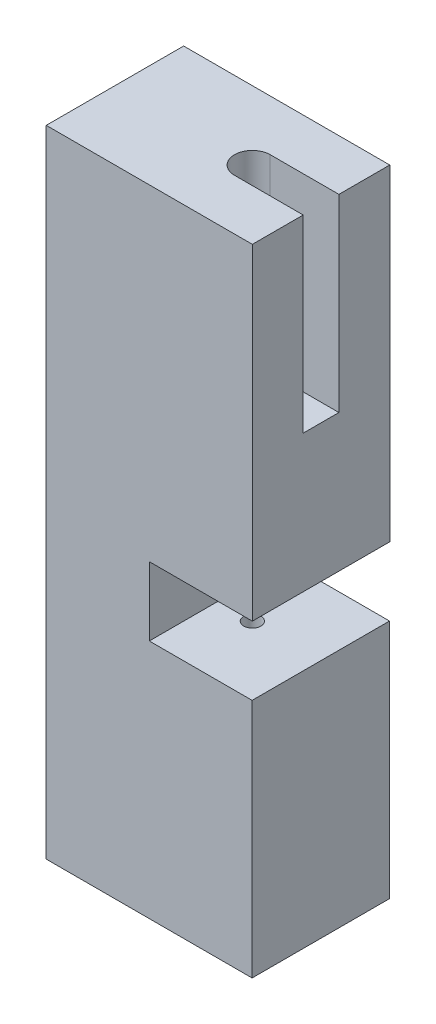
SolidWorks part; units mm, degrees
ref_plane "Front Plane" through (0, 0, 0) normal (0, 0, 1) x (1, 0, 0)
ref_plane "Top Plane" through (0, 0, 0) normal (0, 1, 0) x (1, 0, 0)
ref_plane "Right Plane" through (0, 0, 0) normal (1, 0, 0) x (0, 0, -1)
sketch "Sketch1" plane through (0, 0, 0) normal (0, 1, 0) x (1, 0, 0)
  line L1 (-19.05, -12.7) -> (19.05, -12.7)
  line L2 (-19.05, -12.7) -> (-19.05, 12.7)
  line L3 (-19.05, 12.7) -> (19.05, 12.7)
  line L4 (19.05, -12.7) -> (19.05, 12.7)
  line L5 (-19.05, -12.7) -> (19.05, 12.7) construction
  line L6 (-19.05, 12.7) -> (19.05, -12.7) construction
  point P0 (0, 0)
extrude "Boss-Extrude1" add sketch "Sketch1" along normal blind 25.4
sketch "Sketch2" plane through (0, 25.4, 0) normal (0, 1, 0) x (1, 0, 0)
  line L1 (19.05, -12.7) -> (19.05, 12.7) construction
  line L2 (19.05, 0) -> (6.35, 0) construction
  circle A0 centre (6.35, 0) radius 3.18
sketch "Sketch3" plane through (-19.05, 0, 0) normal (-1, 0, 0) x (0, 0, 1)
  line L0 (0, 0) -> (0, 25.4) construction
  line L1 (-12.7, 25.4) -> (12.7, 25.4) construction
  line L2 (12.7, 12.7) -> (-12.7, 12.7) construction
  line L3 (12.7, 25.4) -> (12.7, 0) construction
  line L4 (-12.7, 25.4) -> (-12.7, 0) construction
  circle A0 centre (0, 12.7) radius 1.5875
extrude "Cut-Extrude2" cut sketch "Sketch3" against normal blind 25.4
hole_wizard "1/4-28 Tapped Hole1" positions "Sketch5" profile "Sketch4" tap size "1/4-28" standard "ANSI Inch"
sketch "Sketch5" plane through (-19.05, 0, 0) normal (-1, 0, 0) x (0, 0, 1)
  point P0 (0, 12.7)
sketch "Sketch4" plane through (-19.05, 12.7, 0) normal (0, 1, 0) x (0, 0, 1)
  line L0 (0, 0) -> (0, 18.8554)
  line L1 (0, 18.8554) -> (2.7051, 17.23)
  line L2 (2.7051, 17.23) -> (2.7051, 0)
  line L5 (2.7051, 0) -> (0, 0)
  line L10 (0, 18.8554) -> (-2.7051, 17.23) construction
  line L11 (0, -6.35) -> (0, 107.95) construction
  dimension "Tap Drill Dia." = 5.4102
  dimension "Tap Drill Depth" = 17.23
  dimension "Drill Angle" = 118
cosmetic thread "Hole Thread1" parameters "D1"=12.7, "D2"=6.35
extrude "Cut-Extrude6" cut sketch "Sketch2" against normal blind 15.875 contours A0
sketch "Sketch8" plane through (0, 0, 0) normal (0, -1, 0) x (1, 0, 0)
  circle A0 centre (6.35, 0) radius 1.5875
extrude "Cut-Extrude7" cut sketch "Sketch8" against normal through all
sketch "Sketch9" plane through (0, 0, 0) normal (0, -1, 0) x (1, 0, 0)
  line L0 (0, -12.7) -> (0, 12.7)
  line L1 (19.05, -12.7) -> (-19.05, -12.7) construction
  line L2 (-19.05, 12.7) -> (19.05, 12.7) construction
  line L3 (0, 12.7) -> (-19.05, 12.7)
  line L4 (-19.05, 12.7) -> (-19.05, -12.7)
  line L5 (-19.05, -12.7) -> (0, -12.7)
extrude "Boss-Extrude2" add sketch "Sketch9" along normal blind 12.7
sketch "Sketch12" plane through (0, -12.7, 0) normal (0, -1, 0) x (1, 0, 0)
  line L0 (-19.05, -12.7) -> (19.005, -12.7)
  line L1 (19.005, -12.7) -> (19.005, 12.7)
  line L2 (19.005, 12.7) -> (-19.05, 12.7)
  line L3 (-19.05, 12.7) -> (-19.05, -12.7)
extrude "Boss-Extrude3" add sketch "Sketch12" along normal blind 44.45 contours L0 L1 L2 L3
sketch "Sketch14" plane through (0, -12.7, 0) normal (0, 1, 0) x (1, 0, 0)
  line L0 (19.005, 0) -> (0, 0) construction
  line L1 (19.005, 12.7) -> (19.005, -12.7) construction
  line L2 (0, 12.7) -> (0, -12.7) construction
  circle A0 centre (6.35, 0) radius 1.5875
extrude "Cut-Extrude8" cut sketch "Sketch14" against normal blind 44.45
hole_wizard "1/4-28 Tapped Hole2" positions "Sketch16" profile "Sketch15" tap size "1/4-28" standard "ANSI Inch"
sketch "Sketch16" plane through (0, -57.15, 0) normal (0, -1, 0) x (-1, 0, 0)
  point P0 (-6.35, 0)
sketch "Sketch15" plane through (6.35, -57.15, 0) normal (1, 0, 0) x (0, 0, -1)
  line L0 (0, 0) -> (0, 18.8554)
  line L1 (0, 18.8554) -> (2.7051, 17.23)
  line L2 (2.7051, 17.23) -> (2.7051, 0)
  line L5 (2.7051, 0) -> (0, 0)
  line L10 (0, 18.8554) -> (-2.7051, 17.23) construction
  line L11 (0, -6.35) -> (0, 107.95) construction
  dimension "Tap Drill Dia." = 5.4102
  dimension "Tap Drill Depth" = 17.23
  dimension "Drill Angle" = 118
cosmetic thread "Hole Thread2" parameters "D1"=12.7, "D2"=6.35
sketch "Sketch24" plane through (0, 25.4, 0) normal (0, 1, 0) x (1, 0, 0)
  line L0 (6.35, -3.302) -> (19.05, -3.302)
  line L1 (19.05, -12.7) -> (19.05, 12.7) construction
  line L7 (6.35, 3.302) -> (19.05, 3.302)
  line L8 (19.05, 3.302) -> (19.05, 12.7)
  line L9 (19.05, -3.302) -> (19.05, -12.7)
  line L10 (19.05, -12.7) -> (-19.05, -12.7)
  line L11 (-19.05, -12.7) -> (-19.05, 12.7)
  line L12 (-19.05, 12.7) -> (19.05, 12.7)
  arc A1 (6.35, 3.302) -> (6.35, -3.302) centre (6.35, 0) ccw
extrude "Boss-Extrude6" add sketch "Sketch24" along normal blind 34.925
